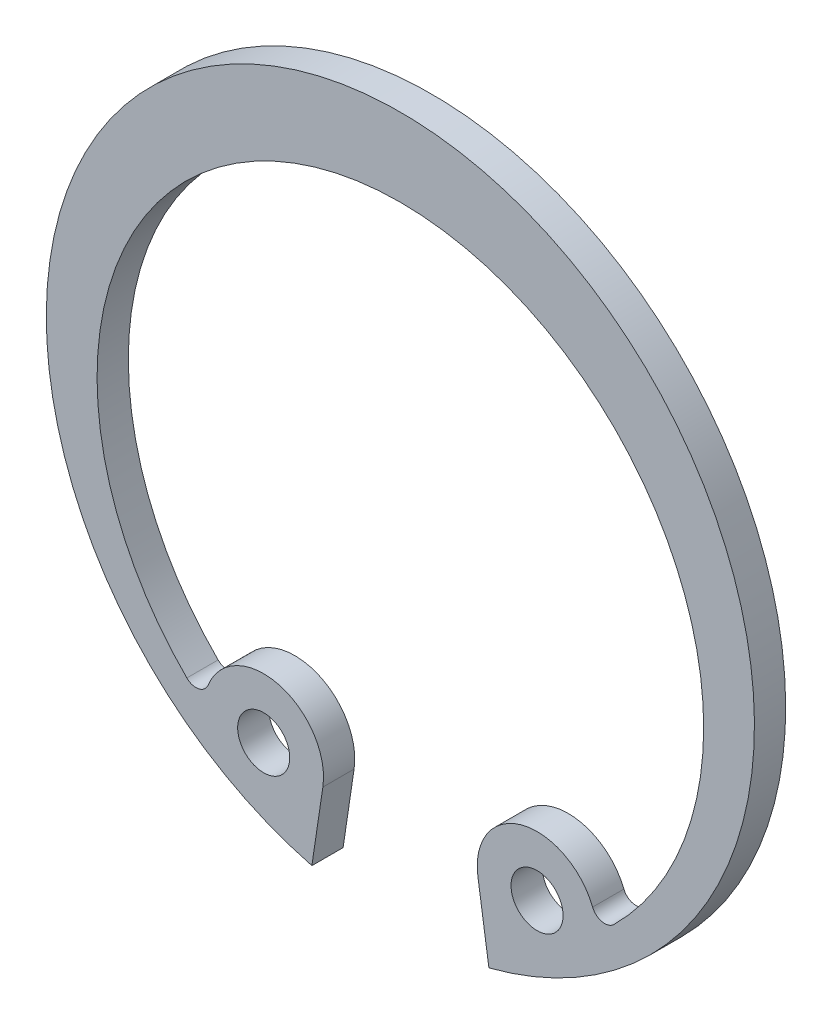
SolidWorks part; units mm, degrees
ref_plane "Front Plane" through (0, 0, 0) normal (0, 0, 1) x (1, 0, 0)
ref_plane "Top Plane" through (0, 0, 0) normal (0, 1, 0) x (1, 0, 0)
ref_plane "Right Plane" through (0, 0, 0) normal (1, 0, 0) x (0, 0, -1)
sketch "Sketch1" plane through (0, 0, 0) normal (0, 0, 1) x (1, 0, 0)
  line L0 (0, 0) -> (0, 13.6) construction
  line L1 (-2.9778, -10.3431) -> (-3.4, -13.1681)
  line L2 (2.9778, -10.3431) -> (3.4, -13.1681)
  line L3 (4.1824, -7.9692) -> (6.32, -12.0423) construction
  arc A0 (3.4, -13.1681) -> (-3.4, -13.1681) centre (0, 0) ccw
  arc A1 (-8.2012, -9.3243) -> (-7.3846, -9.154) centre (-7.8492, -8.9691) ccw
  circle A2 centre (-5.25, -10.0035) radius 1
  circle A3 centre (5.25, -10.0035) radius 1
  circle A4 centre (0, 0) radius 8 construction
  arc A6 (-2.9778, -10.3431) -> (-7.3846, -9.154) centre (-5.25, -10.0035) ccw
  arc A7 (7.3846, -9.154) -> (2.9778, -10.3431) centre (5.25, -10.0035) ccw
  arc A8 (8.2012, -9.3243) -> (-8.2012, -9.3243) centre (0, -1.05) ccw
  arc A9 (8.2012, -9.3243) -> (7.3846, -9.154) centre (7.8492, -8.9691) cw
  point P13 (0, 10.6)
  dimension "D1" = 0.5
  dimension "RIC_D2_s" = 27.2
  dimension "D2" = 17
  dimension "RIC_D4_s" = 23.3
  dimension "RIC_D0_s" = 2
  dimension "RIC_D5_s" = 16
  dimension "RIC_B_s" = 3
  dimension "RIC_MSM_2" = 10.5
  dimension "RIC_MSM_1" = 6.8
  dimension "RIC_A_s" = 4.6
extrude "Boss-Extrude1" add sketch "Sketch1" along normal blind 1.2
equation "\"RIC_D4_s@Sketch1\"=\"RIC_D2_s@Sketch1\"-1.3*\"RIC_B_s@Sketch1\""
